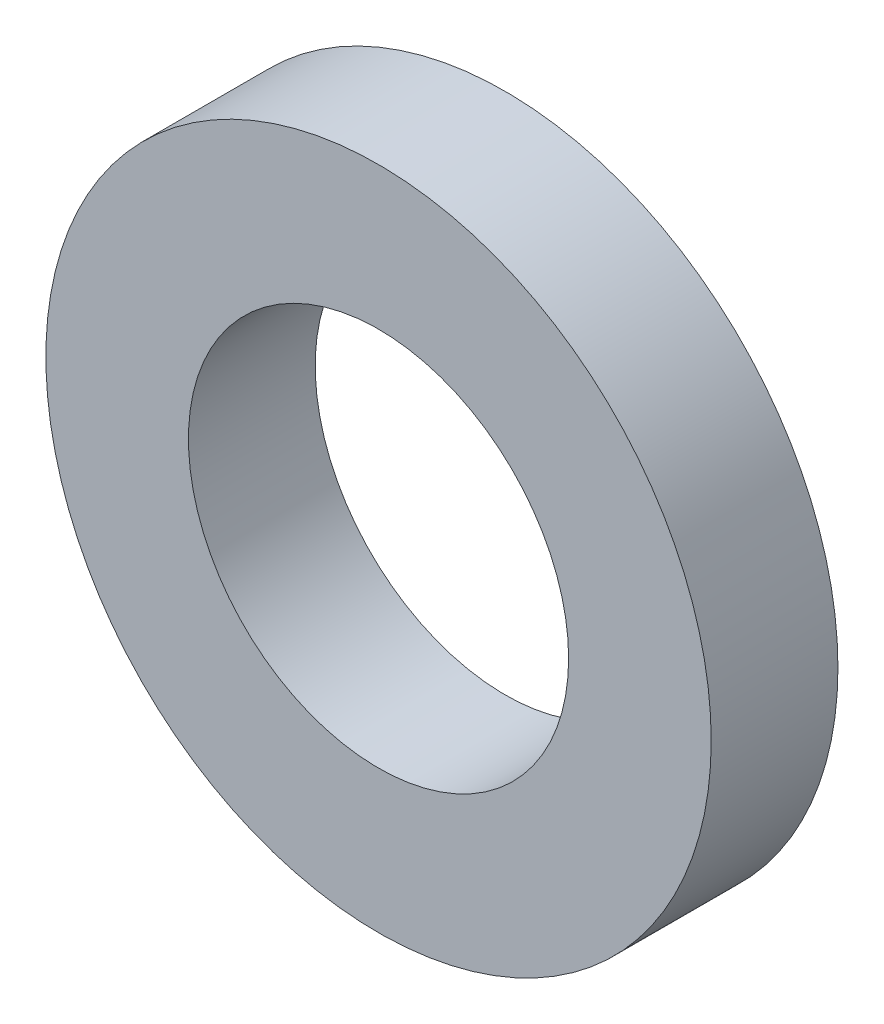
SolidWorks part; units mm, degrees
ref_plane "Front Plane" through (0, 0, 0) normal (0, 0, 1) x (1, 0, 0)
ref_plane "Top Plane" through (0, 0, 0) normal (0, 1, 0) x (1, 0, 0)
ref_plane "Right Plane" through (0, 0, 0) normal (1, 0, 0) x (0, 0, -1)
sketch "Sketch1" plane through (0, 0, 0) normal (0, 0, 1) x (1, 0, 0)
  circle A0 centre (0, 0) radius 5.25
  dimension "D1" = 10.5
extrude "Boss-Extrude1" add sketch "Sketch1" along normal blind 2
sketch "Sketch2" plane through (0, 0, 2) normal (0, 0, 1) x (1, 0, 0)
  circle A0 centre (0, 0) radius 3
  dimension "D1" = 6
extrude "Cut-Extrude1" cut sketch "Sketch2" against normal blind 2
